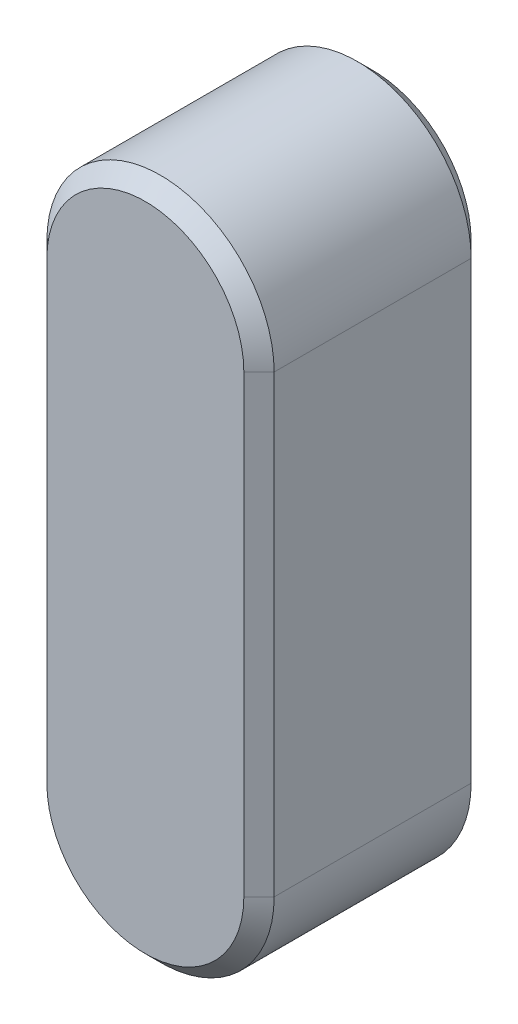
SolidWorks part; units mm, degrees
ref_plane "Front Plane" through (0, 0, 0) normal (0, 0, 1) x (1, 0, 0)
ref_plane "Top Plane" through (0, 0, 0) normal (0, 1, 0) x (1, 0, 0)
ref_plane "Right Plane" through (0, 0, 0) normal (1, 0, 0) x (0, 0, -1)
sketch "Sketch2" plane through (0, 0, 0) normal (0, 0, 1) x (1, 0, 0)
  line L0 (0, 0) -> (0, 6) construction
  line L1 (-1.5, 0) -> (-1.5, 6)
  line L2 (1.5, 0) -> (1.5, 6)
  arc A0 (-1.5, 0) -> (1.5, 0) centre (0, 0) ccw
  arc A1 (1.5, 6) -> (-1.5, 6) centre (0, 6) ccw
  point P3 (0, 3)
  dimension "D1" = 1.5
  dimension "D2" = 6
extrude "Boss-Extrude2" add sketch "Sketch2" along normal blind 3
chamfer "Chamfer3" distance 0.2 angle 45 8 edges at (1.5, 3, 0) (0, 7.5, 0) (-1.5, 3, 0) (0, -1.5, 0) (-1.5, 3, 3) (0, 7.5, 3) (1.5, 3, 3) (0, -1.5, 3)
